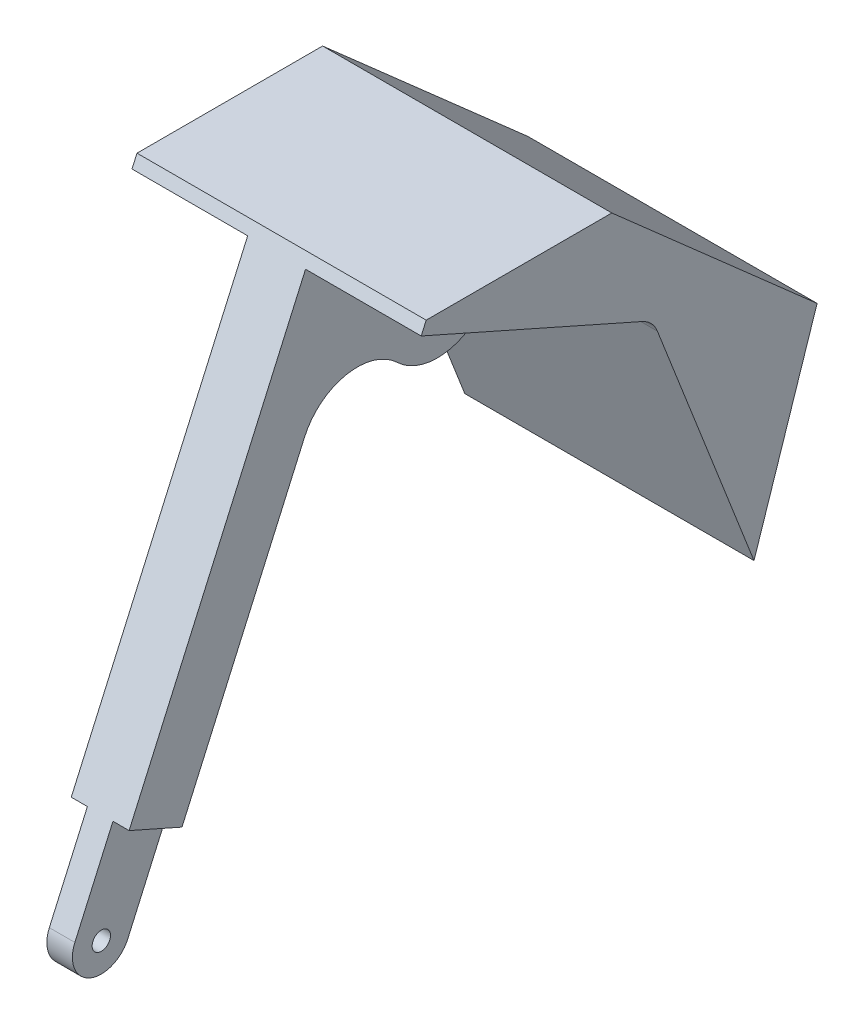
SolidWorks part; units mm, degrees
ref_plane "Front Plane" through (0, 0, 0) normal (0, 0, 1) x (1, 0, 0)
ref_plane "Top Plane" through (0, 0, 0) normal (0, 1, 0) x (1, 0, 0)
ref_plane "Right Plane" through (0, 0, 0) normal (1, 0, 0) x (0, 0, -1)
sketch "Sketch1" plane through (0, 0, 0) normal (1, 0, 0) x (0, 0, -1)
  line L0 (-120.2675, 0) -> (10.6634, 168.0063) construction
  line L1 (10.6634, 168.0063) -> (81.6519, 112.6834) construction
  line L3 (-1000, 0) -> (49000, 0) construction
  line L6 (81.6519, 112.6834) -> (59.8366, 46.5694)
  line L8 (10.6634, 175.2482) -> (81.6519, 112.6834)
  line L9 (-120.2675, 0) -> (-9.6217, 141.9771) construction
  line L10 (-9.6217, 141.9771) -> (-9.6217, 0) construction
  line L15 (26.4188, 131.9956) -> (59.8366, 46.5694)
  line L17 (-53.5149, 175.2482) -> (10.6634, 175.2482)
  line L19 (-55.5924, 121.2135) -> (-111.1256, -4.0528)
  line L20 (-129.4094, 4.0528) -> (-53.5149, 175.2482)
  circle A0 centre (-120.2675, 0) radius 3.175
  circle A1 centre (-9.6217, 141.9771) radius 3.175
  arc A2 (-23.4651, 127.5425) -> (8.1968, 132.8941) centre (-9.6217, 141.9771) ccw
  arc A3 (-129.4094, 4.0528) -> (-111.1256, -4.0528) centre (-120.2675, 0) ccw
  arc A4 (-23.4651, 127.5425) -> (-55.5924, 121.2135) centre (-37.3086, 113.1078) ccw
  arc A5 (26.4188, 131.9956) -> (8.1968, 132.8941) centre (17.106, 128.3525) ccw
  circle A6 centre (-9.6217, 141.9771) radius 20 construction
  dimension "D4" = 6.35
  dimension "D8" = 6.35
  dimension "D10" = 20
  dimension "D5" = 20
  dimension "D6" = 10
  dimension "D9" = 20
  dimension "D1" = 90
  dimension "D2" = 213
  dimension "D3" = 90
  dimension "D7" = 180
extrude "Boss-Extrude1" add sketch "Sketch1" along normal mid plane 100
sketch "Sketch3" plane through (0, -60.9615, 158.2316) normal (0, -0.4053, -0.9142) x (1, 0, 0)
  line L1 (50, -254.1303) -> (10, -254.1303)
  line L2 (50, -254.1303) -> (50, -45.7864)
  line L3 (50, -45.7864) -> (4.4137, -45.7864)
  line L4 (10, -254.1303) -> (10, -103.6056)
  line L7 (0, -1000) -> (0, 49000) construction
  line L13 (10, -103.6056) -> (4.4137, -103.6056)
  line L14 (4.4137, -103.6056) -> (4.4137, -45.7864)
  line L16 (-50, -254.1303) -> (-50, -45.7864)
  line L17 (-50, -254.1303) -> (-10, -254.1303)
  line L18 (-10, -254.1303) -> (-10, -103.6056)
  line L19 (-10, -103.6056) -> (-4.4137, -103.6056)
  line L20 (-4.4137, -103.6056) -> (-4.4137, -45.7864)
  line L21 (-50, -45.7864) -> (-4.4137, -45.7864)
  dimension "D1" = 20
extrude "Cut-Extrude2" cut sketch "Sketch3" along normal blind 85
sketch "Sketch4" plane through (0, 0, 0) normal (1, 0, 0) x (0, 0, -1)
  line L0 (-15.3687, 153.6879) -> (12.0571, 141.5295)
  line L1 (-15.3687, 153.6879) -> (-39.2712, 99.7709)
  line L2 (12.0571, 141.5295) -> (-11.8455, 87.6124)
  line L3 (-39.2712, 99.7709) -> (-11.8455, 87.6124)
  line L4 (22.4688, 136.9137) -> (-55.2375, 171.3626) construction
  circle A0 centre (-9.6217, 141.9771) radius 3.175 construction
  circle A1 centre (-9.6217, 141.9771) radius 3.175 construction
  arc A2 (-23.4651, 127.5425) -> (8.1968, 132.8941) centre (-9.6217, 141.9771) ccw construction
  dimension "D1" = 10
extrude "Cut-Extrude3" cut sketch "Sketch4" against normal mid plane 10
